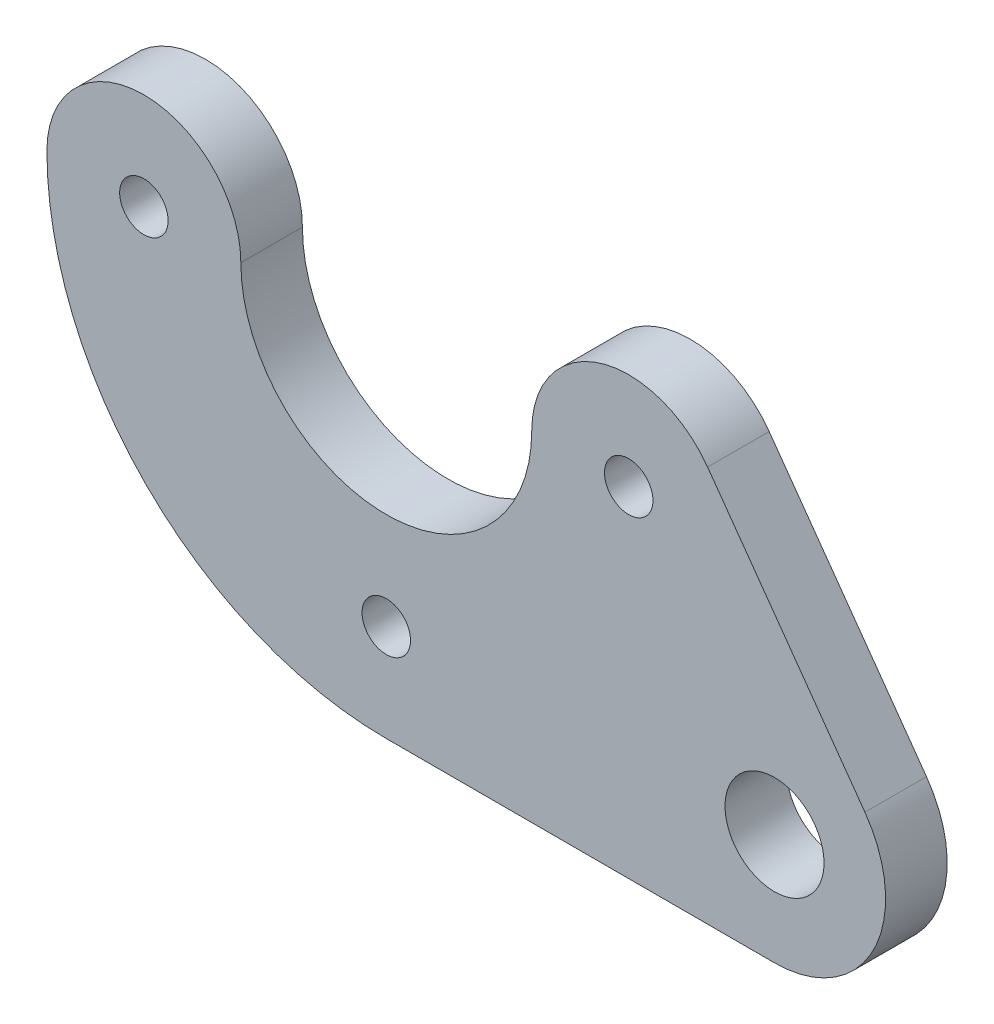
SolidWorks part; units mm, degrees
material "Polypropylene"
ref_plane "Front Plane" through (0, 0, 0) normal (0, 0, 1) x (1, 0, 0)
ref_plane "Top Plane" through (0, 0, 0) normal (0, 1, 0) x (1, 0, 0)
ref_plane "Right Plane" through (0, 0, 0) normal (1, 0, 0) x (0, 0, -1)
sketch "Sketch1" plane through (0, 0, 0) normal (0, 0, 1) x (1, 0, 0)
  line L0 (16.5687, 2.9061) -> (24.6802, -8.4503)
  line L1 (-0.0062, -17.5) -> (20.0173, -17.5071)
  circle A0 centre (0, 0) radius 12.5 construction
  circle A2 centre (12.5, 0) radius 1.25
  circle A3 centre (0, -12.5) radius 1.25
  circle A4 centre (-12.5, 0) radius 1.25
  arc A5 (-12.5, 0) -> (12.5, 0) centre (0, 0) ccw construction
  arc A6 (-17.5, 0) -> (-0.0062, -17.5) centre (0, 0) ccw
  arc A7 (-7.5, 0) -> (7.5, 0) centre (0, 0) ccw
  arc A8 (-7.5, 0) -> (-17.5, 0) centre (-12.5, 0) ccw
  arc A9 (16.5687, 2.9061) -> (7.5, 0) centre (12.5, 0) ccw
  circle A10 centre (20.0193, -11.7794) radius 2.5527
  arc A11 (20.0173, -17.5071) -> (24.6802, -8.4503) centre (20.0193, -11.7794) ccw
  arc A12 (-16.6513, -5.3837) -> (-0.0062, -17.5) centre (0, 0) ccw construction
  point P4 (0, -12.5)
  dimension "D1" = 25
  dimension "D2" = 2.5
  dimension "D4" = 5.1054
  dimension "D5" = 3.175
  dimension "D6" = 12.5
extrude "Boss-Extrude1" add sketch "Sketch1" along normal blind 3.175
